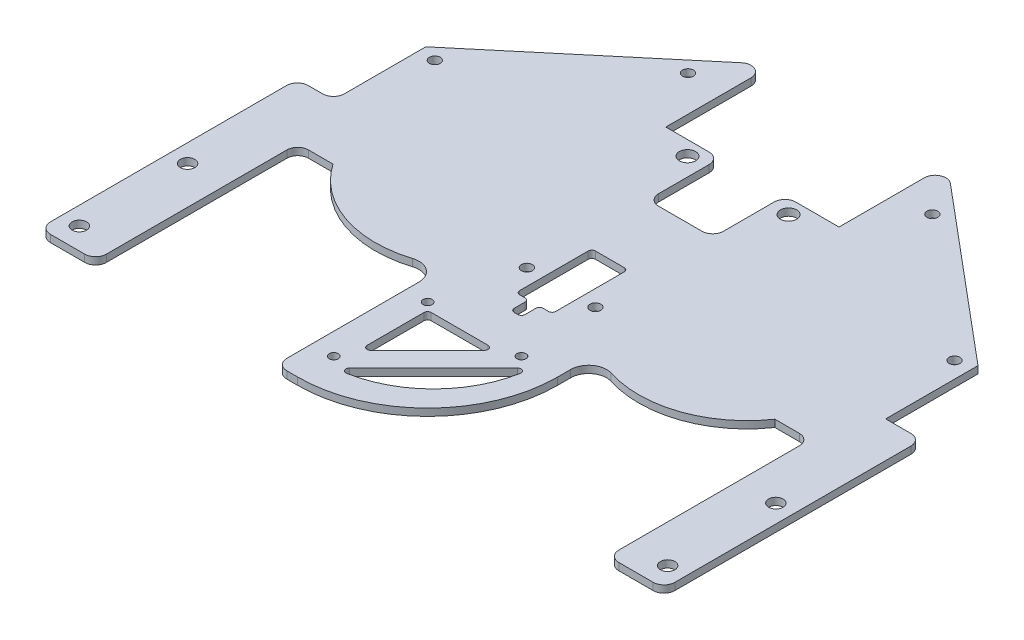
SolidWorks part; units mm, degrees
material "Thornel Mat VMA"
ref_plane "前视基准面" through (0, 0, 0) normal (0, 0, 1) x (1, 0, 0)
ref_plane "上视基准面" through (0, 0, 0) normal (0, 1, 0) x (1, 0, 0)
ref_plane "右视基准面" through (0, 0, 0) normal (1, 0, 0) x (0, 0, -1)
sketch "草图1" plane through (0, 0, 0) normal (0, 1, 0) x (1, 0, 0)
  line L1 (-76.5, 48.5) -> (76.5, 48.5)
  line L2 (-76.5, 48.5) -> (-76.5, -48.5)
  line L3 (-76.5, -48.5) -> (76.5, -48.5)
  line L4 (76.5, 48.5) -> (76.5, -48.5)
  line L5 (0, -48.5) -> (0, 48.5) construction
  line L6 (-76.5, 0) -> (76.5, 0) construction
  point P0 (0, 0)
  dimension "D1" = 153
  dimension "D2" = 97
extrude "凸台-拉伸1" add sketch "草图1" along normal blind 2
sketch "草图2" plane through (0, 0, 0) normal (0, 1, 0) x (1, 0, 0)
  line L0 (0, -48.5) -> (0, 235.4683) construction
  line L1 (-76.5, -48.5) -> (76.5, -48.5) construction
  line L2 (76.5, 48.5) -> (-76.5, 48.5) construction
  line L3 (-15, 104.5) -> (15, 104.5)
  line L4 (-15, 104.5) -> (-15, 48.5)
  line L5 (-15, 48.5) -> (15, 48.5)
  line L6 (15, 104.5) -> (15, 48.5)
  line L7 (0, 48.5) -> (0, 104.5) construction
  line L8 (-15, 76.5) -> (15, 76.5) construction
  point P5 (0, 76.5)
  dimension "D1" = 153
  dimension "D2" = 30
extrude "凸台-拉伸2" add sketch "草图2" along normal blind 2
sketch "草图3" plane through (0, 2, 0) normal (0, 1, 0) x (1, 0, 0)
  line L0 (-76.5, 48.5) -> (-15, 100.1)
  line L1 (-15, 104.5) -> (-15, 48.5) construction
  line L2 (-15, 100.1) -> (-15, 48.5)
  line L3 (-15, 48.5) -> (-76.5, 48.5)
  line L4 (-76.5, -48.5) -> (76.5, -48.5) construction
  line L5 (0, 104.5) -> (0, -48.5) construction
  line L6 (15, 104.5) -> (-15, 104.5) construction
  line L7 (15, 100.1) -> (15, 48.5)
  line L8 (15, 48.5) -> (76.5, 48.5)
  line L9 (76.5, 48.5) -> (15, 100.1)
  dimension "D1" = 148.6
extrude "凸台-拉伸3" add sketch "草图3" against normal blind 2
sketch "草图4" plane through (0, 2, 0) normal (0, 1, 0) x (1, 0, 0)
  line L0 (0, 104.5) -> (0, -48.5) construction
  line L1 (-86.5, -6.5) -> (-76.5, -6.5)
  line L2 (-86.5, -6.5) -> (-86.5, -48.5)
  line L3 (-86.5, -48.5) -> (-76.5, -48.5)
  line L4 (-76.5, -6.5) -> (-76.5, -48.5)
  line L5 (-81.5, -48.5) -> (-81.5, -6.5) construction
  line L6 (-86.5, -27.5) -> (-76.5, -27.5) construction
  line L7 (15, 104.5) -> (-15, 104.5) construction
  line L8 (-76.5, -48.5) -> (76.5, -48.5) construction
  line L9 (86.5, -27.5) -> (76.5, -27.5) construction
  line L10 (81.5, -48.5) -> (81.5, -6.5) construction
  line L11 (76.5, -6.5) -> (76.5, -48.5)
  line L12 (86.5, -48.5) -> (76.5, -48.5)
  line L13 (86.5, -6.5) -> (86.5, -48.5)
  line L14 (86.5, -6.5) -> (76.5, -6.5)
  circle A0 centre (-81.5, -12.5) radius 2
  circle A1 centre (-81.5, -42.5) radius 2
  circle A2 centre (81.5, -42.5) radius 2
  circle A3 centre (81.5, -12.5) radius 2
  point P0 (-81.5, -27.5)
  point P18 (81.5, -27.5)
  dimension "D3" = 4
  dimension "D4" = 30
  dimension "D1" = 42
  dimension "D2" = 10
extrude "凸台-拉伸4" add sketch "草图4" against normal blind 2
sketch "草图6" plane through (0, 2, 0) normal (0, 1, 0) x (1, 0, 0)
  line L0 (0, 104.5) -> (0, -48.5) construction
  line L1 (15, 104.5) -> (-15, 104.5) construction
  line L2 (-86.5, -48.5) -> (86.5, -48.5) construction
  circle A0 centre (14, 58.5) radius 2.25
  circle A1 centre (-14, 58.5) radius 2.25
  dimension "D1" = 4.5
  dimension "D2" = 28
  dimension "D3" = 46
extrude "切除-拉伸1" cut sketch "草图6" against normal blind 2
sketch "草图7" plane through (0, 2, 0) normal (0, 1, 0) x (1, 0, 0)
  line L0 (-86.5, -48.5) -> (86.5, -48.5) construction
  line L1 (-71, 7.5) -> (-21, 7.5)
  line L2 (-71, 7.5) -> (-71, -48.5)
  line L3 (-71, -48.5) -> (-21, -48.5)
  line L4 (-21, 7.5) -> (-21, -48.5)
  line L5 (-46, -48.5) -> (-46, 7.5) construction
  line L6 (-71, -20.5) -> (-21, -20.5) construction
  line L7 (0, 104.5) -> (0, -48.5) construction
  line L8 (15, 104.5) -> (-15, 104.5) construction
  line L9 (71, -20.5) -> (21, -20.5) construction
  line L10 (46, -48.5) -> (46, 7.5) construction
  line L11 (21, 7.5) -> (21, -48.5)
  line L12 (71, -48.5) -> (21, -48.5)
  line L13 (71, 7.5) -> (71, -48.5)
  line L14 (71, 7.5) -> (21, 7.5)
  point P0 (-46, -20.5)
  point P18 (46, -20.5)
  dimension "D1" = 46
  dimension "D2" = 50
  dimension "D3" = 56
extrude "切除-拉伸2" cut sketch "草图7" against normal blind 2
sketch "草图8" plane through (0, 2, 0) normal (0, 1, 0) x (1, 0, 0)
  line L0 (-14, 58.5) -> (14, 58.5) construction
  line L1 (0, 104.5) -> (0, -48.5) construction
  line L2 (15, 104.5) -> (-15, 104.5) construction
  line L3 (-21, -48.5) -> (21, -48.5) construction
  line L4 (-24, 62.5) -> (24, 62.5)
  line L5 (-24, 62.5) -> (-24, 124.9842)
  line L6 (-24, 124.9842) -> (24, 124.9842)
  line L7 (24, 124.9842) -> (24, 62.5)
  point P14 (0, 62.5)
  dimension "D1" = 48
  dimension "D2" = 4
extrude "切除-拉伸3" cut sketch "草图8" against normal blind 2
fillet "圆角3" radius 3 8 edges at (-71, 1, 48.5) (-21, 1, 48.5) (-21, 1, -7.5) (-71, 1, -7.5) (71, 1, 48.5) (71, 1, -7.5) (21, 1, -7.5) (21, 1, 48.5)
sketch "草图9" plane through (0, 2, 0) normal (0, 1, 0) x (1, 0, 0)
  line L0 (-76.5, 48.5) -> (-76.5, -6.5) construction
  line L1 (-86.5, -6.5) -> (-76.5, -6.5)
  line L2 (-86.5, -6.5) -> (-86.5, 22.9202)
  line L3 (-86.5, 22.9202) -> (-76.5, 22.9202)
  line L4 (-76.5, -6.5) -> (-76.5, 22.9202)
  line L5 (0, 95.0628) -> (0, -69.9815) construction
  line L6 (76.5, -6.5) -> (76.5, 22.9202)
  line L7 (86.5, 22.9202) -> (76.5, 22.9202)
  line L8 (86.5, -6.5) -> (86.5, 22.9202)
  line L9 (86.5, -6.5) -> (76.5, -6.5)
extrude "凸台-拉伸5" add sketch "草图9" against normal blind 2
fillet "圆角4" radius 3 2 edges at (-76.5, 1, -22.9202) (-86.5, 1, -22.9202)
sketch "草图10" plane through (0, 2, 0) normal (0, 1, 0) x (1, 0, 0)
  line L0 (0, 62.5) -> (0, -48.5) construction
  line L1 (-24, 62.5) -> (24, 62.5) construction
  line L2 (-18, -48.5) -> (18, -48.5) construction
  line L4 (-9, 42.5) -> (9, 42.5)
  line L5 (-9, 42.5) -> (-9, 62.5)
  line L6 (-9, 62.5) -> (9, 62.5)
  line L7 (9, 42.5) -> (9, 62.5)
  line L8 (0, 62.5) -> (0, 42.5) construction
  line L9 (-9, 52.5) -> (9, 52.5) construction
  point P7 (0, 52.5)
  dimension "D1" = 18
  dimension "D2" = 20
extrude "切除-拉伸4" cut sketch "草图10" against normal blind 2
fillet "圆角5" radius 3 6 edges at (9, 1, -42.5) (-9, 1, -42.5) (24, 1, -92.5488) (-24, 1, -92.5488) (9, 1, -62.5) (-9, 1, -62.5)
sketch "草图11" plane through (0, 2, 0) normal (0, 1, 0) x (1, 0, 0)
  line L0 (0, 98.773) -> (0, -79.3783) construction
  line L1 (-81.5, -12.5) -> (-81.5, -42.5) construction
  line L2 (81.5, -12.5) -> (81.5, -42.5) construction
  line L3 (81.5, -27.5) -> (-81.5, -27.5) construction
  line L4 (-36.5, 24.5) -> (36.5, 24.5) construction
  circle A0 centre (-36.5, 24.5) radius 30
  circle A1 centre (36.5, 24.5) radius 30
  dimension "D1" = 73
  dimension "D3" = 60
  dimension "D2" = 52
extrude "凸台-拉伸6" add sketch "草图11" against normal blind 2
fillet "圆角6" radius 3 3 edges at (86.5, 1, -22.9202) (86.5, 1, 48.5) (-86.5, 1, 48.5)
sketch "草图12" plane through (0, 2, 0) normal (0, 1, 0) x (1, 0, 0)
  line L0 (-81.5, -12.5) -> (-81.5, -42.5) construction
  line L1 (-15, -12.5) -> (11, -12.5) construction
  line L2 (81.5, -12.5) -> (81.5, -42.5) construction
  line L3 (11, -12.5) -> (11, -38.5) construction
  line L4 (11, -38.5) -> (-15, -38.5) construction
  line L5 (-15, -38.5) -> (-15, -12.5) construction
  line L6 (-81.5, -27.5) -> (81.5, -27.5) construction
  line L7 (-2, -12.5) -> (-2, -38.5) construction
  line L8 (-33.8219, -25.5) -> (33.8395, -25.5) construction
  line L9 (0, 113.6461) -> (0, -56.4469) construction
  circle A0 centre (11, -12.5) radius 1.25
  circle A1 centre (-15, -12.5) radius 1.25
  circle A2 centre (-15, -38.5) radius 1.25
  dimension "D1" = 2.5
  dimension "D2" = 26
  dimension "D3" = 26
  dimension "D6" = 2.5
  dimension "D4" = 2
  dimension "D5" = 2
extrude "切除-拉伸5" cut sketch "草图12" against normal blind 2
sketch "草图13" plane through (0, 2, 0) normal (0, 1, 0) x (1, 0, 0)
  line L0 (-76.5, 48.5) -> (76.5, 48.5) construction
  line L1 (0, 116.36) -> (0, -81.3827) construction
  circle A0 centre (-72, 46.5) radius 1.5
  circle A1 centre (72, 46.5) radius 1.5
  dimension "D1" = 3
  dimension "D2" = 72
  dimension "D3" = 2
extrude "切除-拉伸6" cut sketch "草图13" against normal blind 10
sketch "草图14" plane through (0, 2, 0) normal (0, 1, 0) x (1, 0, 0)
  line L0 (-72, 46.5) -> (-33.8605, 78.5) construction
  line L1 (-28.9283, 88.4138) -> (-76.5, 48.5) construction
  line L2 (0, 109.2093) -> (0, -61.6038) construction
  circle A1 centre (-33.8605, 78.5) radius 1.5
  circle A2 centre (-72, 46.5) radius 1.5 construction
  circle A3 centre (33.8605, 78.5) radius 1.5
  dimension "D1" = 3
  dimension "D2" = 32
extrude "切除-拉伸7" cut sketch "草图14" against normal blind 10
sketch "草图15" plane through (0, 2, 0) normal (0, 1, 0) x (1, 0, 0)
  line L0 (-15, -12.5) -> (21, -12.5) construction
  line L1 (-15, -12.5) -> (-15, -48.5) construction
  line L2 (21, -12.5) -> (21, -48.5)
  line L3 (-15, -48.5) -> (21, -48.5)
  arc A0 (-15, -48.5) -> (21, -12.5) centre (-15, -12.5) ccw
extrude "切除-拉伸8" cut sketch "草图15" against normal blind 10
fillet "圆角7" radius 5 2 edges at (21, 1, 1.1856) (-21, 1, 1.1856)
sketch "草图16" plane through (0, 2, 0) normal (0, 1, 0) x (1, 0, 0)
  line L0 (0, 89.353) -> (0, -54.3698) construction
  line L2 (-24, 62.5) -> (-12, 62.5) construction
  circle A0 centre (9.5, 9.5) radius 1.5
  circle A1 centre (-9.5, 9.5) radius 1.5
  dimension "D1" = 19
  dimension "D2" = 53
  dimension "D3" = 3
extrude "切除-拉伸9" cut sketch "草图16" against normal blind 10
sketch "草图17" plane through (0, 2, 0) normal (0, 1, 0) x (1, 0, 0)
  line L0 (0, 149.5856) -> (0, -99.7876) construction
  line L1 (-24, 62.5) -> (-12, 62.5) construction
  line L2 (-5, 23) -> (5, 23)
  line L3 (-5, 23) -> (-5, 2)
  line L4 (-5, 2) -> (5, 2)
  line L5 (5, 23) -> (5, 2)
  line L6 (0, 2) -> (0, 23) construction
  line L7 (-5, 12.5) -> (5, 12.5) construction
  point P3 (0, 12.5)
  point P7 (0, 21.0216)
  dimension "D1" = 21
  dimension "D2" = 10
  dimension "D3" = 50
extrude "切除-拉伸10" cut sketch "草图17" against normal blind 10
fillet "圆角8" radius 1 4 edges at (5, 1, -2) (-5, 1, -2) (5, 1, -23) (-5, 1, -23)
sketch "草图18" plane through (0, 2, 0) normal (0, 1, 0) x (1, 0, 0)
  line L0 (0, 96.5655) -> (0, -63.3059) construction
  line L1 (-4, 2) -> (4, 2) construction
  line L2 (-1.5, -3) -> (1.5, -3)
  line L3 (-1.5, -3) -> (-1.5, 2)
  line L4 (-1.5, 2) -> (1.5, 2)
  line L5 (1.5, -3) -> (1.5, 2)
  line L6 (0, 2) -> (0, -3) construction
  line L7 (-1.5, -0.5) -> (1.5, -0.5) construction
  point P3 (0, -0.5)
  dimension "D1" = 5
  dimension "D2" = 3
extrude "切除-拉伸11" cut sketch "草图18" against normal blind 10
fillet "圆角9" radius 1 4 edges at (-1.5, 1, 3) (1.5, 1, 3) (1.5, 1, -2) (-1.5, 1, -2)
sketch "草图19" plane through (0, 2, 0) normal (0, 1, 0) x (1, 0, 0)
  line L0 (-15, -12.5) -> (11, -12.5) construction
  line L1 (11, -12.5) -> (-15, -38.5) construction
  line L2 (-15, -38.5) -> (-15, -12.5) construction
  line L3 (-13, -14.5) -> (-13, -33.6716)
  line L4 (-13, -33.6716) -> (6.1716, -14.5)
  line L5 (6.1716, -14.5) -> (-13, -14.5)
  dimension "D1" = 2
  dimension "D2" = 4
  dimension "D3" = 2
extrude "切除-拉伸12" cut sketch "草图19" against normal blind 2
fillet "圆角10" radius 1 3 edges at (-13, 1, 14.5) (6.1716, 1, 14.5) (-13, 1, 33.6716)
sketch "草图21" plane through (0, 2, 0) normal (0, 1, 0) x (1, 0, 0)
  line L0 (-15, -12.5) -> (11, -12.5) construction
  line L1 (11, -12.5) -> (-15, -38.5) construction
  line L2 (-15, -38.5) -> (-15, -12.5) construction
  line L3 (15.3548, -13.8021) -> (-12.0779, -41.2347)
  arc A0 (-12.0779, -41.2347) -> (15.3548, -13.8021) centre (-14.5437, -11.3363) ccw
  circle A1 centre (-15, -12.5) radius 1.25 construction
  dimension "D1" = 60
  dimension "D2" = 4
extrude "切除-拉伸13" cut sketch "草图21" against normal blind 2
fillet "圆角11" radius 1 2 edges at (15.3548, 1, 13.8021) (-12.0779, 1, 41.2347)
